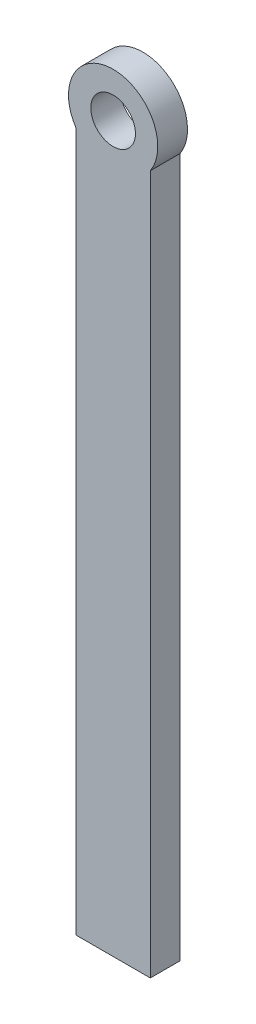
SolidWorks part; units mm, degrees
ref_plane "Front Plane" through (0, 0, 0) normal (0, 0, 1) x (1, 0, 0)
ref_plane "Top Plane" through (0, 0, 0) normal (0, 1, 0) x (1, 0, 0)
ref_plane "Right Plane" through (0, 0, 0) normal (1, 0, 0) x (0, 0, -1)
sketch "Sketch3" plane through (0, 0, 0) normal (0, 0, 1) x (1, 0, 0)
  line L0 (-25, -16.5831) -> (-25, -486.5831)
  line L1 (-25, -486.5831) -> (25, -486.5831)
  line L2 (25, -486.5831) -> (25, -16.5831)
  line L3 (0, 20.7057) -> (0, -22.2746) construction
  circle A0 centre (0, 0) radius 15
  arc A2 (-25, -16.5831) -> (25, -16.5831) centre (0, 0) cw
  point P9 (0, 0)
  point P10 (0, 0)
  point P11 (0, 0)
  point P12 (18.4673, -21.455)
  dimension "D1" = 30
  dimension "D2" = 30
  dimension "D3" = 470
  dimension "D4" = 50
extrude "Boss-Extrude1" add sketch "Sketch3" along normal blind 20
